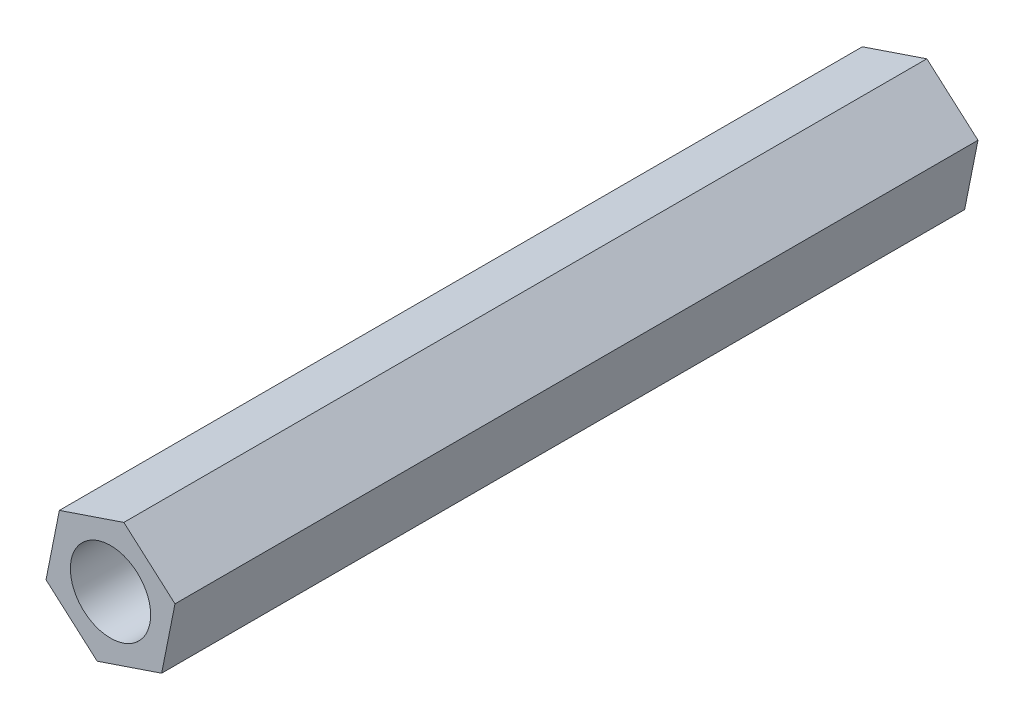
SolidWorks part; units mm, degrees
ref_plane "前视基准面" through (0, 0, 0) normal (0, 0, 1) x (1, 0, 0)
ref_plane "上视基准面" through (0, 0, 0) normal (0, 1, 0) x (1, 0, 0)
ref_plane "右视基准面" through (0, 0, 0) normal (1, 0, 0) x (0, 0, -1)
sketch "草图1" plane through (0, 0, 0) normal (0, 0, 1) x (1, 0, 0)
  line L1 (2.0384, -1.7911) -> (2.5704, 0.8698)
  line L2 (2.5704, 0.8698) -> (0.5319, 2.6609)
  line L3 (0.5319, 2.6609) -> (-2.0384, 1.7911)
  line L4 (-2.0384, 1.7911) -> (-2.5704, -0.8698)
  line L5 (-2.5704, -0.8698) -> (-0.5319, -2.6609)
  line L6 (-0.5319, -2.6609) -> (2.0384, -1.7911)
  circle A0 centre (0, 0) radius 2.35 construction
  circle A1 centre (0, 0) radius 1.6
  dimension "D1" = 3.2
  dimension "D2" = 4.7
extrude "凸台-拉伸1" add sketch "草图1" along normal blind 32
